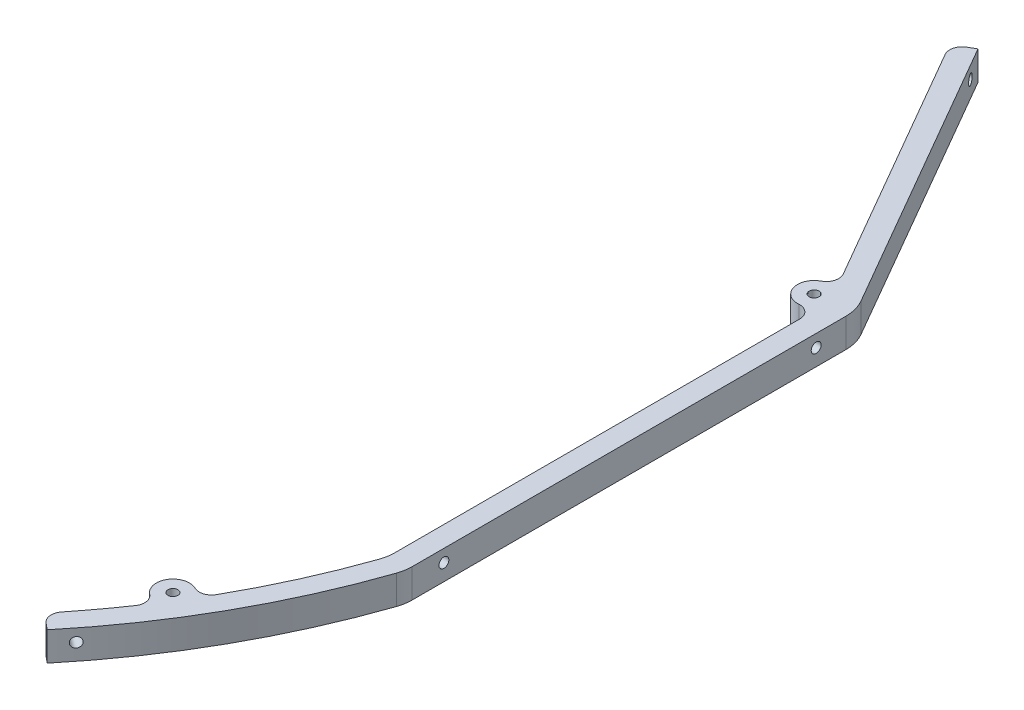
SolidWorks part; units mm, degrees
material "ABS"
ref_plane "Plan de face" through (0, 0, 0) normal (0, 0, 1) x (1, 0, 0)
ref_plane "Plan de dessus" through (0, 0, 0) normal (0, 1, 0) x (1, 0, 0)
ref_plane "Plan de droite" through (0, 0, 0) normal (1, 0, 0) x (0, 0, -1)
sketch "Esquisse1" plane through (0, 0, 0) normal (0, 1, 0) x (1, 0, 0)
  line L0 (163.5, -54.3149) -> (163.5, 54.8397)
  line L1 (163.5, 54.8397) -> (123.5, 124.1218)
  line L2 (158.5, -53.5) -> (158.5, 53.5)
  line L3 (158.5, 53.5) -> (119.1699, 121.6218)
  line L4 (165, -54.557) -> (165, 55.2417) construction
  line L5 (163.5, 54.8397) -> (103.2187, 159.25) construction
  line L6 (158.5, 53.5) -> (98.8886, 156.75) construction
  line L7 (123.5, 124.1218) -> (119.1699, 121.6218)
  line L8 (132.5985, -110) -> (128.7503, -106.8076)
  line L12 (0, 160) -> (104.5177, 160) construction
  line L13 (165, 55.2417) -> (104.5177, 160) construction
  arc A0 (132.5985, -110) -> (163.5, -54.3149) centre (0, 0) ccw
  arc A1 (128.7503, -106.8076) -> (158.5, -53.5) centre (0, 0) ccw
  arc A2 (111.9744, -130.9354) -> (163.5, -54.3149) centre (0, 0) ccw construction
  arc A3 (108.7248, -127.1355) -> (158.5, -53.5) centre (0, 0) ccw construction
  arc A5 (0, -145) -> (112.9493, -132.0754) centre (0, 355) ccw construction
  arc A6 (112.9493, -132.0754) -> (165, -54.557) centre (0, 0) ccw construction
  dimension "D1" = 1.5
  dimension "D2" = 5
  dimension "D3" = 80
  dimension "D4" = 110
extrude "Boss.-Extru.1" add sketch "Esquisse1" along normal blind 7
sketch "Esquisse2" plane through (0, 7, 0) normal (0, 1, 0) x (1, 0, 0)
  circle A0 centre (155, 53) radius 1.2
  circle A1 centre (155, 53) radius 4
  circle A2 centre (140, -87) radius 4
  circle A3 centre (140, -87) radius 1.2
  dimension "D1" = 155
  dimension "D2" = 53
  dimension "D3" = 2.4
  dimension "D4" = 8
  dimension "D5" = 140
  dimension "D6" = 87
extrude "Boss.-Extru.2" add sketch "Esquisse2" against normal up to surface (7 mm away) up to face at (144.1333, 0, -3.3315)
fillet "Congé1" radius 10 3 edges at (158.5, 3.5, 53.5) (163.5, 3.5, 54.3149) (163.5, 3.5, -54.8397)
fillet "Congé2" radius 3 6 edges at (128.7503, 3.5, 106.8076) (119.1699, 3.5, -121.6218) (140.3809, 3.5, 90.9818) (143.7388, 3.5, 85.5783) (156.6976, 3.5, -56.6219) (158.5, 3.5, -51.0635)
hole_wizard "Diamètre du perçage Ø2.4 (2.4)1" positions "Esquisse3D1" profile "Esquisse3" hole size "Ø2.4" standard "ISO" end condition through all
sketch3d "Esquisse3D1"
  line L0 (163.5, 0, 52.6725) -> (163.5, 0, -52.1603) construction
  line L1 (132.5985, 7, 110) -> (132.5985, 0, 110) construction
  line L2 (162.1603, 0, -57.1603) -> (123.5, 0, -124.1218) construction
  line L3 (123.5, 7, -124.1218) -> (123.5, 0, -124.1218) construction
  point P0 (135.7347, 4, 106.1059)
  point P2 (163.5, 4, -45)
  point P4 (163.5, 4, 45)
  point P6 (126, 4, -119.7917)
  dimension "D1" = 4
  dimension "D2" = 4
  dimension "D3" = 4
  dimension "D4" = 5
  dimension "D5" = 45
  dimension "D6" = 45
  dimension "D7" = 4
  dimension "D8" = 5
sketch "Esquisse3" plane through (135.7347, 4, 106.1059) normal (0, 1, 0) x (0.6159, 0, -0.7878)
  line L0 (0, 0) -> (0, 153.9761)
  line L1 (0, 153.9761) -> (1.2, 153.9761)
  line L2 (1.2, 153.9761) -> (1.2, 0)
  line L5 (1.2, 0) -> (0, 0)
  line L11 (0, -6.35) -> (0, 107.95) construction
  dimension "Diamètre du perçage jusqu'au prochain" = 2.4
  dimension "Profondeur du perçage jusqu'au prochain" = 153.9761
